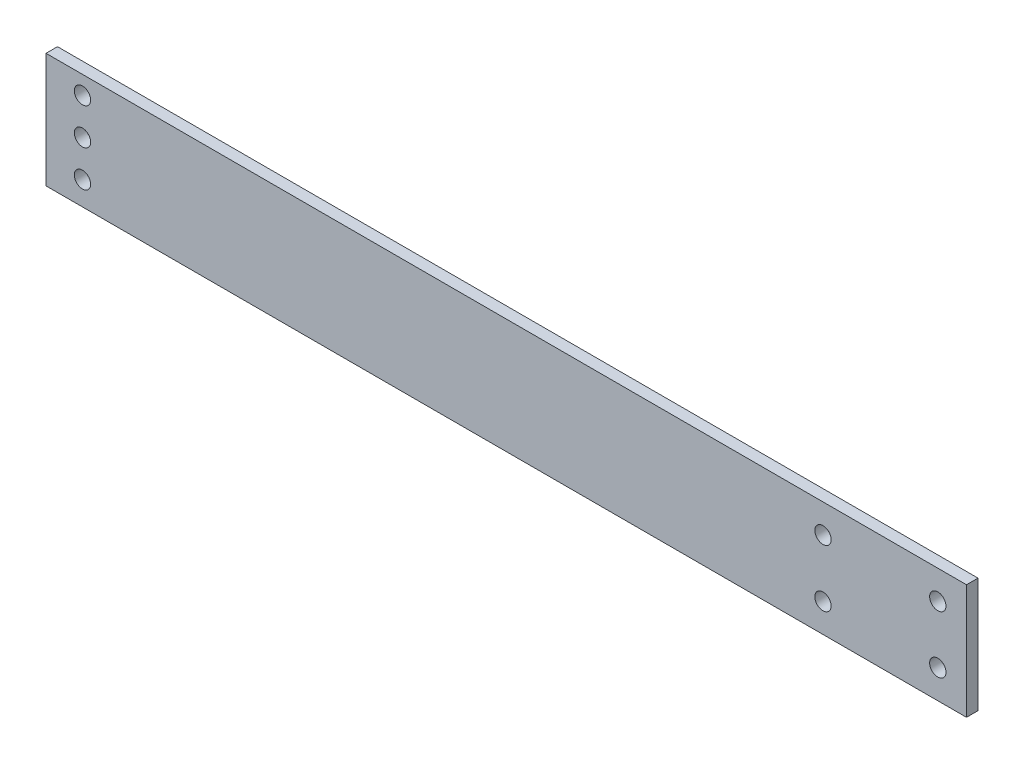
SolidWorks part; units mm, degrees
ref_plane "Front Plane" through (0, 0, 0) normal (0, 0, 1) x (1, 0, 0)
ref_plane "Top Plane" through (0, 0, 0) normal (0, 1, 0) x (1, 0, 0)
ref_plane "Right Plane" through (0, 0, 0) normal (1, 0, 0) x (0, 0, -1)
sketch "Sketch1" plane through (0, 0, 0) normal (0, 0, 1) x (1, 0, 0)
  line L1 (-80.155, -10) -> (80.155, -10)
  line L2 (-80.155, -10) -> (-80.155, 10)
  line L3 (-80.155, 10) -> (80.155, 10)
  line L4 (80.155, -10) -> (80.155, 10)
  line L5 (-80.155, -10) -> (80.155, 10) construction
  line L6 (-80.155, 10) -> (80.155, -10) construction
  point P0 (0, 0)
  dimension "D1" = 160.31
  dimension "D2" = 20
extrude "Boss-Extrude1" add sketch "Sketch1" along normal blind 2
sketch "Sketch2" plane through (0, 0, 2) normal (0, 0, 1) x (1, 0, 0)
  line L0 (80.155, 10) -> (-80.155, 10) construction
  line L1 (-80.155, 10) -> (-80.155, -10) construction
  line L2 (-73.805, 6.825) -> (-73.805, 0.475) construction
  line L3 (80.155, -10) -> (80.155, 10) construction
  line L4 (75.155, 5) -> (55.155, 5) construction
  circle A0 centre (-73.805, 6.825) radius 1.4224
  circle A2 centre (-73.805, 0.475) radius 1.4224
  circle A3 centre (-73.805, -5.875) radius 1.4224
  circle A4 centre (75.155, 5) radius 1.4224
  circle A5 centre (55.155, 5) radius 1.4224
  circle A6 centre (55.155, -5) radius 1.4224
  circle A7 centre (75.155, -5) radius 1.4224
  dimension "D1" = 2.8448
  dimension "D6" = 2.8448
  dimension "D2" = 3.175
  dimension "D3" = 6.35
  dimension "D5" = 6.35
  dimension "D7" = 5
  dimension "D8" = 5
  dimension "D11" = 20
  dimension "D4" = 3
  dimension "D9" = 2
  dimension "D10" = 2
extrude "Cut-Extrude1" cut sketch "Sketch2" against normal up to next
